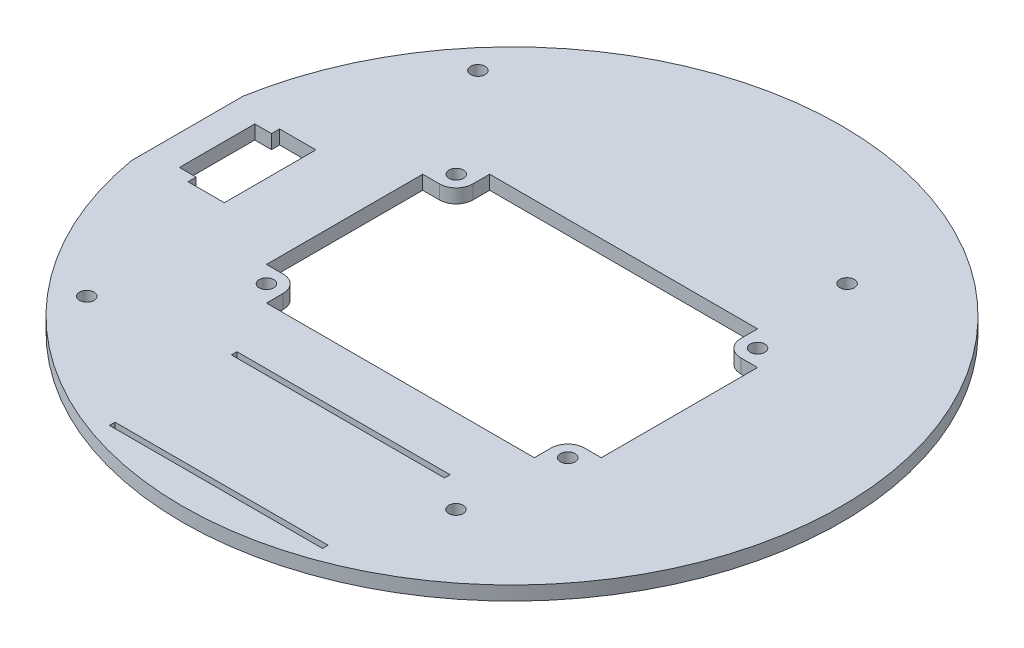
SolidWorks part; units mm, degrees
ref_plane "Front Plane" through (0, 0, 0) normal (0, 0, 1) x (1, 0, 0)
ref_plane "Top Plane" through (0, 0, 0) normal (0, 1, 0) x (1, 0, 0)
ref_plane "Right Plane" through (0, 0, 0) normal (1, 0, 0) x (0, 0, -1)
sketch "Sketch1" plane through (0, 0, 0) normal (0, 1, 0) x (1, 0, 0)
  line L0 (-73.9169, 12.7) -> (-73.9169, -12.7)
  line L1 (34.29, 21.59) -> (34.29, 17.78) construction
  line L2 (34.29, -21.59) -> (30.48, -21.59) construction
  line L3 (-34.29, -21.59) -> (-34.29, -17.78) construction
  line L4 (-34.29, 21.59) -> (-30.48, 21.59) construction
  line L5 (0, -75) -> (0, -21.59) construction
  line L6 (-73.9169, 0) -> (-34.29, 0) construction
  line L7 (0, 25.4) -> (0, -25.4) construction
  line L8 (-38.1, 0) -> (38.1, 0) construction
  line L9 (34.29, -17.78) -> (34.29, -21.59) construction
  line L10 (-30.48, -21.59) -> (-34.29, -21.59) construction
  line L11 (-34.29, 17.78) -> (-34.29, 21.59) construction
  line L12 (-73.9169, 0) -> (-67.1149, 0) construction
  line L13 (-30.48, 21.59) -> (-30.48, 25.4)
  line L14 (-30.48, 25.4) -> (30.48, 25.4)
  line L15 (30.48, 21.59) -> (30.48, 25.4)
  line L16 (34.29, 17.78) -> (38.1, 17.78)
  line L17 (-67.1149, 8.5725) -> (-63.3049, 8.5725)
  line L18 (34.29, -17.78) -> (38.1, -17.78)
  line L19 (38.1, 17.78) -> (38.1, -17.78)
  line L20 (-67.1149, 8.5725) -> (-67.1149, -8.5725)
  line L21 (30.48, -21.59) -> (30.48, -25.4)
  line L22 (30.48, -25.4) -> (-30.48, -25.4)
  line L23 (-30.48, -21.59) -> (-30.48, -25.4)
  line L24 (-34.29, -17.78) -> (-38.1, -17.78)
  line L25 (-67.1149, -8.5725) -> (-63.3049, -8.5725)
  line L26 (-34.29, 17.78) -> (-38.1, 17.78)
  line L27 (-38.1, -17.78) -> (-38.1, 17.78)
  line L28 (30.48, 21.59) -> (34.29, 21.59) construction
  line L29 (-55.0499, 8.5725) -> (-55.0499, -8.5725)
  line L30 (-63.3049, 8.5725) -> (-63.3049, 10.414)
  line L31 (-63.3049, 10.414) -> (-55.0499, 10.414)
  line L32 (-55.0499, 10.414) -> (-55.0499, 8.5725)
  line L33 (-63.3049, -8.5725) -> (-63.3049, -10.414)
  line L34 (-63.3049, -10.414) -> (-55.0499, -10.414)
  line L35 (-55.0499, -10.414) -> (-55.0499, -8.5725)
  line L36 (0, -38.34) -> (0, -25.4) construction
  line L37 (-24.25, -39.61) -> (24.25, -39.61)
  line L38 (-24.25, -39.61) -> (-24.25, -38.34)
  line L39 (-24.25, -38.34) -> (24.25, -38.34)
  line L40 (24.25, -39.61) -> (24.25, -38.34)
  line L41 (-24.25, -67.38) -> (24.25, -67.38)
  line L42 (-24.25, -67.38) -> (-24.25, -66.11)
  line L43 (-24.25, -66.11) -> (24.25, -66.11)
  line L44 (24.25, -67.38) -> (24.25, -66.11)
  arc A0 (-73.9169, -12.7) -> (-73.9169, 12.7) centre (0, 0) ccw
  circle A1 centre (-52.2677, -44.5075) radius 1.651
  circle A2 centre (31.75, -44.5075) radius 1.651
  circle A3 centre (31.75, 44.5075) radius 1.651
  circle A4 centre (-52.2677, 44.5075) radius 1.651
  circle A5 centre (-52.2677, -44.5075) radius 1.651 construction
  circle A6 centre (34.29, 21.59) radius 1.651
  circle A8 centre (34.29, -21.59) radius 1.651
  circle A10 centre (-34.29, -21.59) radius 1.651
  circle A12 centre (-34.29, 21.59) radius 1.651
  arc A16 (-30.48, -21.59) -> (-34.29, -17.78) centre (-34.29, -21.59) ccw
  arc A17 (-30.48, 21.59) -> (-34.29, 17.78) centre (-34.29, 21.59) cw
  arc A18 (30.48, 21.59) -> (34.29, 17.78) centre (34.29, 21.59) ccw
  arc A19 (30.48, -21.59) -> (34.29, -17.78) centre (34.29, -21.59) cw
  dimension "D1" = 150
  dimension "D2" = 25.4
  dimension "D3" = 68.58
  dimension "D4" = 43.18
  dimension "D5" = 60.96
  dimension "D6" = 17.145
  dimension "D7" = 50.8
  dimension "D8" = 12.065
  dimension "D9" = 12.065
  dimension "D10" = 3.81
  dimension "D11" = 20.828
  dimension "D12" = 6.802
  dimension "D13" = 7.62
  dimension "D14" = 26.5
  dimension "D15" = 48.5
  dimension "D16" = 1.27
extrude "Boss-Extrude1" add sketch "Sketch1" along normal blind 3.175
equation "\"15c\"=5.81198"
